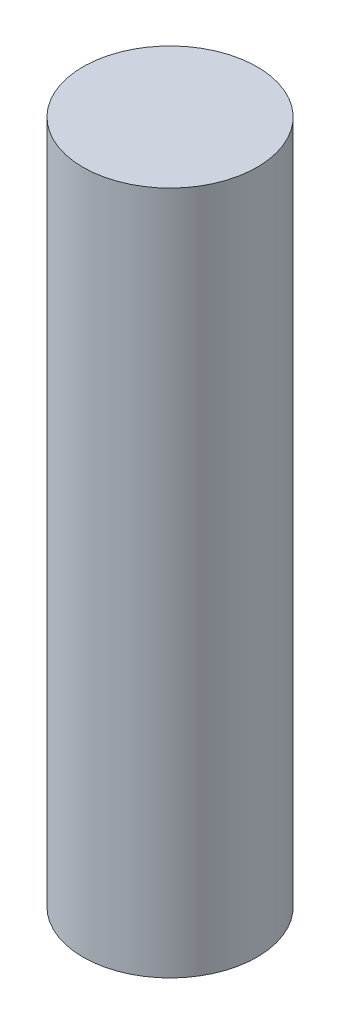
SolidWorks part; units mm, degrees
ref_plane "Front Plane" through (0, 0, 0) normal (0, 0, 1) x (1, 0, 0)
ref_plane "Top Plane" through (0, 0, 0) normal (0, 1, 0) x (1, 0, 0)
ref_plane "Right Plane" through (0, 0, 0) normal (1, 0, 0) x (0, 0, -1)
sketch "Sketch1" plane through (0, 0, 0) normal (0, 1, 0) x (1, 0, 0)
  circle A0 centre (0, 0) radius 3.5
extrude "Boss-Extrude1" add sketch "Sketch1" along normal blind 27.5
